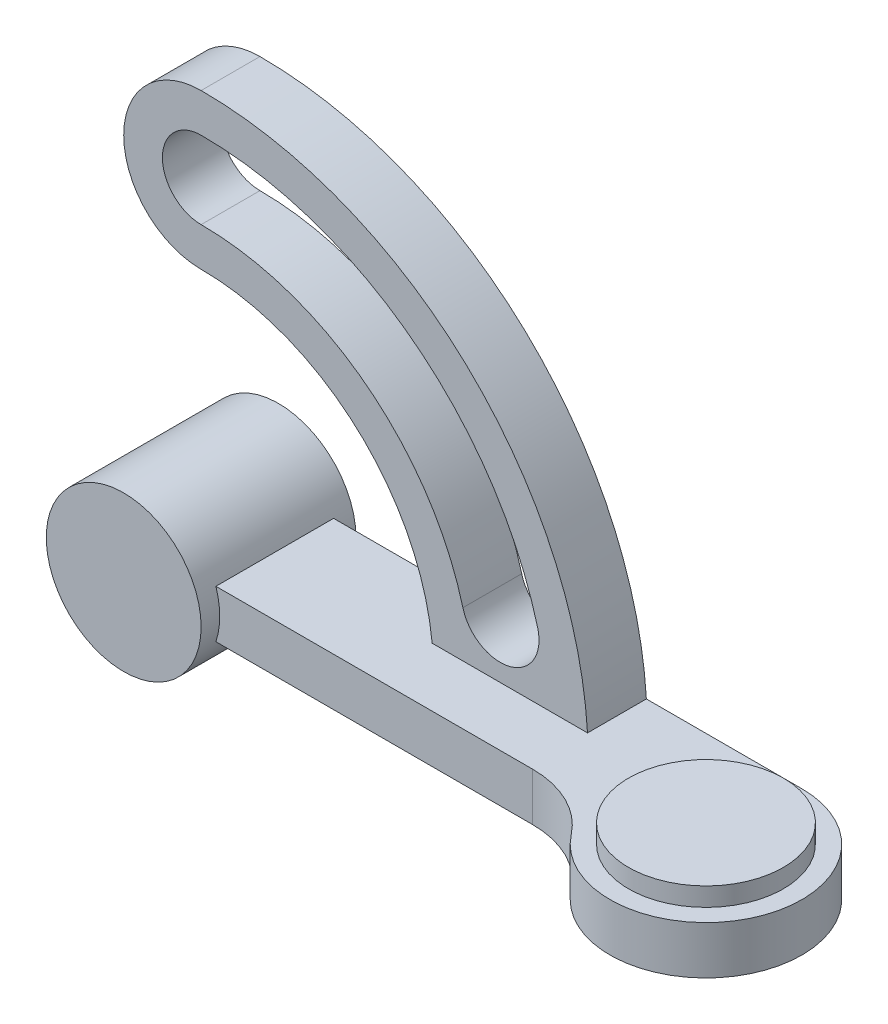
SolidWorks part; units mm, degrees
ref_plane "Alzado" through (0, 0, 0) normal (0, 0, 1) x (1, 0, 0)
ref_plane "Planta" through (0, 0, 0) normal (0, 1, 0) x (1, 0, 0)
ref_plane "Vista lateral" through (0, 0, 0) normal (1, 0, 0) x (0, 0, -1)
sketch "Croquis2" plane through (0, 0, 0) normal (0, 1, 0) x (1, 0, 0)
  line L0 (0, 15.748) -> (-88.9, 15.748)
  line L1 (-88.9, 15.748) -> (-88.9, -3.556)
  line L2 (-88.9, -3.556) -> (-24.8868, -3.556)
  arc A0 (-12.4434, -9.652) -> (0, 15.748) centre (0, 0) ccw
  arc A1 (-12.4434, -9.652) -> (-24.8868, -3.556) centre (-24.8868, -19.304) ccw
  dimension "D1" = 31.496
  dimension "D2" = 88.9
  dimension "D3" = 19.304
extrude "Saliente-Extruir1" add sketch "Croquis2" along normal blind 7.874
ref_plane "Plano1" through (0, 0, -6.096) normal (0, 0, 1) x (1, 0, 0)
sketch "Croquis4" plane through (0, 0, -6.096) normal (0, 0, 1) x (1, 0, 0)
  line L0 (-88.9, 7.874) -> (-88.9, 0) construction
  circle A0 centre (-88.9, 3.937) radius 12.7
  dimension "D1" = 25.4
extrude "Saliente-Extruir2" add sketch "Croquis4" along normal blind 12.7 and the other way blind 12.7
sketch "Croquis8" plane through (0, 0, -6.096) normal (0, 0, 1) x (1, 0, 0)
  line L0 (-88.9, 3.937) -> (-88.9, 54.737) construction
  line L1 (-76.8256, 7.874) -> (-24.8868, 7.874) construction
  line L2 (-51.004, 7.874) -> (-25.5222, 7.874)
  arc A0 (-88.9, 54.737) -> (-38.1, 3.937) centre (-88.9, 3.937) cw construction
  arc A1 (-88.9, 67.437) -> (-88.9, 42.037) centre (-88.9, 54.737) ccw
  arc A2 (-88.9, 67.437) -> (-25.5222, 7.874) centre (-88.9, 3.937) cw
  arc A3 (-88.9, 42.037) -> (-51.004, 7.874) centre (-88.9, 3.937) cw
  dimension "D2" = 25.4
  dimension "D1" = 50.8
extrude "Saliente-Extruir4" add sketch "Croquis8" against normal blind 9.652
sketch "Croquis9" plane through (0, 0, -6.096) normal (0, 0, 1) x (1, 0, 0)
  line L0 (-88.9, 3.937) -> (-88.9, 73.4165) construction
  line L1 (-88.9, 3.937) -> (-22.7704, 21.6564) construction
  line L2 (-101.6, 54.737) -> (-88.9, 54.737) construction
  arc A0 (-88.9, 67.437) -> (-88.9, 42.037) centre (-88.9, 54.737) ccw construction
  arc A1 (-88.9, 54.737) -> (-39.831, 17.085) centre (-88.9, 3.937) cw construction
  arc A2 (-88.9, 61.087) -> (-88.9, 48.387) centre (-88.9, 54.737) ccw
  arc A3 (-45.9646, 15.4415) -> (-33.6973, 18.7285) centre (-39.831, 17.085) ccw
  arc A4 (-88.9, 48.387) -> (-45.9646, 15.4415) centre (-88.9, 3.937) cw
  arc A5 (-88.9, 61.087) -> (-33.6973, 18.7285) centre (-88.9, 3.937) cw
  dimension "D2" = 12.7
  dimension "D1" = 75
extrude "Cortar-Extruir1" cut sketch "Croquis9" against normal blind 9.652
sketch "Croquis10" plane through (0, 7.874, 0) normal (0, 1, 0) x (1, 0, 0)
  circle A0 centre (0, 0) radius 12.7
  dimension "D1" = 25.4
extrude "Saliente-Extruir5" add sketch "Croquis10" along normal blind 3.048
